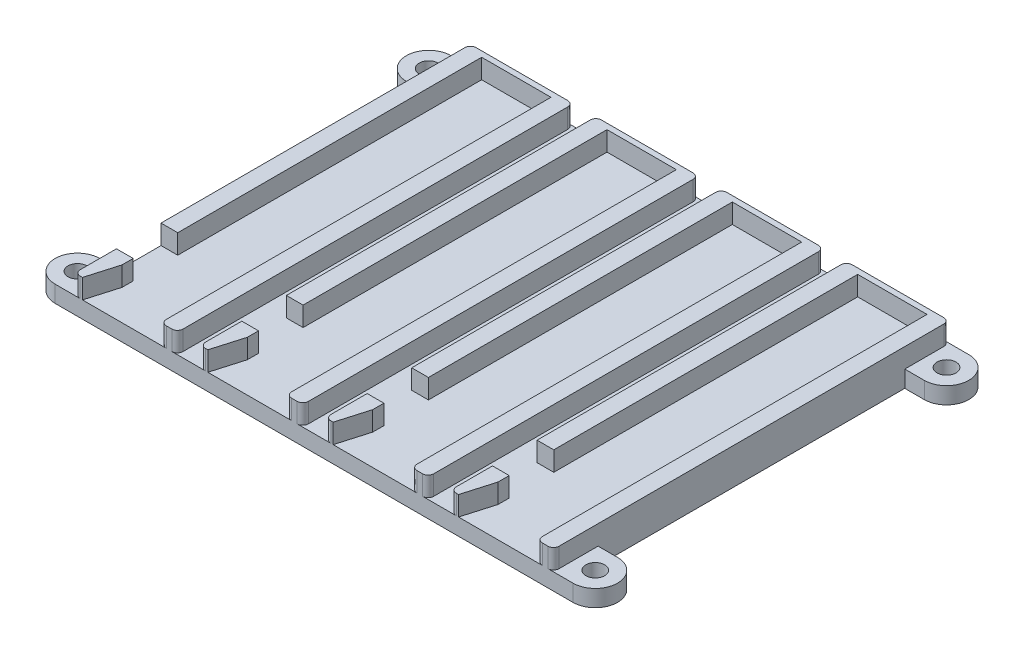
SolidWorks part; units mm, degrees
ref_plane "正面" through (0, 0, 0) normal (0, 0, 1) x (1, 0, 0)
ref_plane "平面" through (0, 0, 0) normal (0, 1, 0) x (1, 0, 0)
ref_plane "右側面" through (0, 0, 0) normal (1, 0, 0) x (0, 0, -1)
sketch "ｽｹｯﾁ2" plane through (0, 0, 0) normal (0, 1, 0) x (1, 0, 0)
  line L0 (85.95, 71.05) -> (89.45, 71.05)
  line L1 (0, 0) -> (85.95, 0)
  line L2 (0, 8) -> (0, 63.05)
  line L3 (0, 71.05) -> (85.95, 71.05)
  line L4 (85.95, 8) -> (85.95, 63.05)
  line L5 (85.95, 63.05) -> (89.45, 63.05)
  line L6 (89.45, 71.05) -> (89.45, 63.05) construction
  line L7 (85.95, 0) -> (89.45, 0)
  line L8 (85.95, 8) -> (89.45, 8)
  line L9 (89.45, 8) -> (89.45, 0) construction
  line L10 (0, 71.05) -> (-3.5, 71.05)
  line L11 (0, 63.05) -> (-3.5, 63.05)
  line L12 (-3.5, 71.05) -> (-3.5, 63.05) construction
  line L13 (0, 0) -> (-3.5, 0)
  line L14 (0, 8) -> (-3.5, 8)
  line L15 (-3.5, 8) -> (-3.5, 0) construction
  arc A0 (89.45, 63.05) -> (89.45, 71.05) centre (89.45, 67.05) ccw
  circle A1 centre (89.45, 67.05) radius 1.7
  arc A2 (89.45, 0) -> (89.45, 8) centre (89.45, 4) ccw
  circle A3 centre (89.45, 4) radius 1.7
  arc A4 (-3.5, 71.05) -> (-3.5, 63.05) centre (-3.5, 67.05) ccw
  circle A5 centre (-3.5, 67.05) radius 1.7
  arc A6 (-3.5, 8) -> (-3.5, 0) centre (-3.5, 4) ccw
  circle A7 centre (-3.5, 4) radius 1.7
  dimension "D3" = 4
  dimension "D4" = 3.4
  dimension "D1" = 71.05
  dimension "D2" = 85.95
  dimension "D5" = 3.5
extrude "ﾎﾞｽ - 押し出し1" add sketch "ｽｹｯﾁ2" along normal blind 3
sketch "ｽｹｯﾁ3" plane through (0, 3, 0) normal (0, 1, 0) x (1, 0, 0)
  line L8 (-3.5, 0) -> (89.45, 0) construction
  line L15 (68.9, 0) -> (70.5, 5.5)
  line L16 (70.5, 5.5) -> (70.5, 7.5)
  line L17 (70.5, 7.5) -> (67.5, 7.5)
  line L18 (67.5, 7.5) -> (67.5, 0)
  line L19 (67.5, 0) -> (68.9, 0)
  line L20 (67.5, 15.5) -> (70.5, 15.5)
  line L21 (70.5, 15.5) -> (70.5, 70.05)
  line L22 (70.5, 70.05) -> (82.95, 70.05)
  line L23 (82.95, 70.05) -> (82.95, 0)
  line L24 (82.95, 0) -> (85.95, 0)
  line L25 (85.95, 0) -> (85.95, 71.05)
  line L26 (85.95, 71.05) -> (67.5, 71.05)
  line L27 (67.5, 71.05) -> (67.5, 15.5)
  line L28 (76.725, 70.05) -> (76.725, 0) construction
  line L67 (45, 15.5) -> (48, 15.5)
  line L68 (48, 15.5) -> (48, 70.05)
  line L69 (48, 70.05) -> (60.45, 70.05)
  line L70 (60.45, 70.05) -> (60.45, 0)
  line L71 (60.45, 0) -> (63.45, 0)
  line L72 (63.45, 0) -> (63.45, 71.05)
  line L73 (63.45, 71.05) -> (45, 71.05)
  line L74 (45, 71.05) -> (45, 15.5)
  line L75 (46.4, 0) -> (48, 5.5)
  line L76 (48, 5.5) -> (48, 7.5)
  line L77 (48, 7.5) -> (45, 7.5)
  line L78 (45, 7.5) -> (45, 0)
  line L79 (45, 0) -> (46.4, 0)
  line L80 (22.5, 15.5) -> (25.5, 15.5)
  line L81 (25.5, 15.5) -> (25.5, 70.05)
  line L82 (25.5, 70.05) -> (37.95, 70.05)
  line L83 (37.95, 70.05) -> (37.95, 0)
  line L84 (37.95, 0) -> (40.95, 0)
  line L85 (40.95, 0) -> (40.95, 71.05)
  line L86 (40.95, 71.05) -> (22.5, 71.05)
  line L87 (22.5, 71.05) -> (22.5, 15.5)
  line L88 (23.9, 0) -> (25.5, 5.5)
  line L89 (25.5, 5.5) -> (25.5, 7.5)
  line L90 (25.5, 7.5) -> (22.5, 7.5)
  line L91 (22.5, 7.5) -> (22.5, 0)
  line L92 (22.5, 0) -> (23.9, 0)
  line L93 (0, 15.5) -> (3, 15.5)
  line L94 (3, 15.5) -> (3, 70.05)
  line L95 (3, 70.05) -> (15.45, 70.05)
  line L96 (15.45, 70.05) -> (15.45, 0)
  line L97 (15.45, 0) -> (18.45, 0)
  line L98 (18.45, 0) -> (18.45, 71.05)
  line L99 (18.45, 71.05) -> (0, 71.05)
  line L100 (0, 71.05) -> (0, 15.5)
  line L101 (1.4, 0) -> (3, 5.5)
  line L102 (3, 5.5) -> (3, 7.5)
  line L103 (3, 7.5) -> (0, 7.5)
  line L104 (0, 7.5) -> (0, 0)
  line L105 (0, 0) -> (1.4, 0)
  line L106 (85.95, 8) -> (85.95, 63.05) construction
  dimension "D1" = 12.45
  dimension "D2" = 1
  dimension "D3" = 7.5
  dimension "D4" = 2
  dimension "D5" = 8
  dimension "D6" = 1.6
  dimension "D7" = 3
  dimension "D8" = 4
  dimension "D9" = 4.05
extrude "ﾎﾞｽ - 押し出し2" add sketch "ｽｹｯﾁ3" along normal blind 3.5
fillet "ﾌｨﾚｯﾄ5" radius 1 20 edges at (0, 4.75, -71.05) (85.95, 4.75, -71.05) (85.95, 4.75, 0) (67.5, 4.75, 0) (67.5, 4.75, -71.05) (63.45, 4.75, -71.05) (45, 4.75, -71.05) (40.95, 4.75, -71.05) (22.5, 4.75, -71.05) (18.45, 4.75, -71.05) (63.45, 4.75, 0) (60.45, 4.75, 0) (45, 4.75, 0) (40.95, 4.75, 0) (37.95, 4.75, 0) (22.5, 4.75, 0) (18.45, 4.75, 0) (15.45, 4.75, 0) (82.95, 4.75, 0) (0, 4.75, 0)
